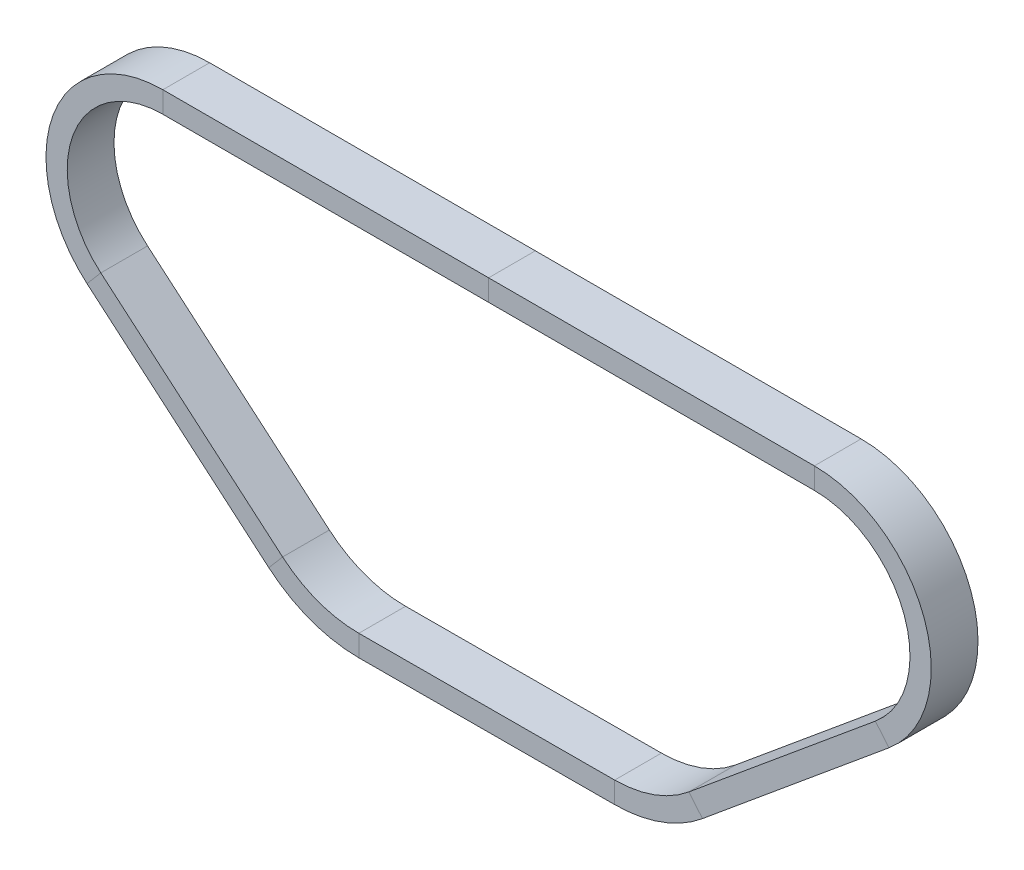
SolidWorks part; units mm, degrees
ref_plane "Front Plane" through (0, 0, 0) normal (0, 0, 1) x (1, 0, 0)
ref_plane "Top Plane" through (0, 0, 0) normal (0, 1, 0) x (1, 0, 0)
ref_plane "Right Plane" through (0, 0, 0) normal (1, 0, 0) x (0, 0, -1)
sketch "Sketch1" plane through (0, 0, 0) normal (0, 0, 1) x (1, 0, 0)
  line L0 (-928.5715, -1.7712) -> (-500.8345, -366.6608)
  line L1 (-305.2172, -438.4238) -> (296.661, -436.5855)
  line L2 (487.1625, -367.5831) -> (925.8354, -4.0717)
  line L3 (766.3206, 438.4252) -> (-766.3206, 438.4252)
  arc A0 (-766.3206, 438.4252) -> (-928.5715, -1.7712) centre (-766.3206, 188.4252) ccw
  arc A1 (-500.8345, -366.6608) -> (-305.2172, -438.4238) centre (-306.1335, -138.4252) ccw
  arc A2 (296.661, -436.5855) -> (487.1625, -367.5831) centre (295.7448, -136.5869) ccw
  arc A3 (925.8354, -4.0717) -> (766.3206, 438.4252) centre (766.3206, 188.4252) ccw
sketch "Sketch2" plane through (0, 0, 0) normal (1, 0, 0) x (0, 0, -1)
  line L0 (0, 438.4252) -> (0, -4.0717) construction
  line L1 (-55, 463.4252) -> (55, 463.4252)
  line L2 (-55, 463.4252) -> (-55, 413.4252)
  line L3 (-55, 413.4252) -> (55, 413.4252)
  line L4 (55, 463.4252) -> (55, 413.4252)
  line L5 (-55, 463.4252) -> (55, 413.4252) construction
  line L6 (-55, 413.4252) -> (55, 463.4252) construction
  point P0 (0, 438.4252)
  dimension "D1" = 50
  dimension "D2" = 110
sweep "Sweep1" add profiles "Sketch2" path "Sketch1"
